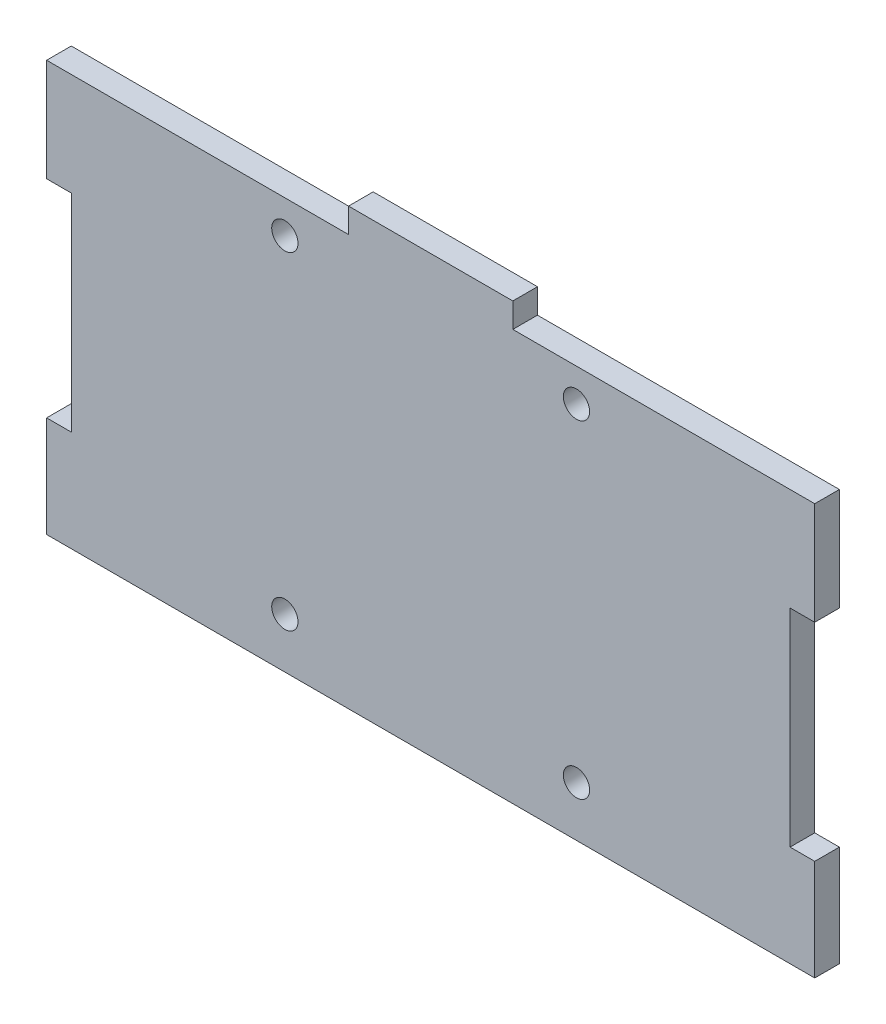
SolidWorks part; units mm, degrees
ref_plane "Plan de face" through (0, 0, 0) normal (0, 0, 1) x (1, 0, 0)
ref_plane "Plan de dessus" through (0, 0, 0) normal (0, 1, 0) x (1, 0, 0)
ref_plane "Plan de droite" through (0, 0, 0) normal (1, 0, 0) x (0, 0, -1)
sketch "Esquisse1" plane through (0, 0, 0) normal (0, 0, 1) x (1, 0, 0)
  line L1 (46.75, -25) -> (-46.75, -25)
  line L2 (46.75, -25) -> (46.75, -12.7)
  line L3 (46.75, 25) -> (26.2, 25)
  line L4 (-46.75, -25) -> (-46.75, -12.7)
  line L5 (46.75, -25) -> (-46.75, 25) construction
  line L6 (46.75, 25) -> (-46.75, -25) construction
  line L18 (0, 42.5868) -> (0, -42.8016) construction
  line L31 (-26.2, 25) -> (-46.75, 25)
  line L32 (23, 25) -> (-23, 25)
  line L33 (-46.75, -12.7) -> (-43.75, -12.7)
  line L34 (46.75, 12.5) -> (43.75, 12.5)
  line L36 (46.75, -12.7) -> (43.75, -12.7)
  line L37 (43.75, 12.5) -> (43.75, -12.7)
  line L38 (-43.75, 12.5) -> (-43.75, -12.7)
  line L39 (-46.75, 12.5) -> (-43.75, 12.5)
  line L41 (-46.75, 12.5) -> (-46.75, 25)
  line L42 (46.75, 12.5) -> (46.75, 25)
  line L43 (-26.2, 25) -> (-23, 25)
  line L44 (23, 25) -> (26.2, 25)
  point P0 (0, 0)
  dimension "D1" = 50
  dimension "D2" = 93.5
  dimension "D15" = 25.2
  dimension "D16" = 3
extrude "Boss.-Extru.1" add sketch "Esquisse1" along normal blind 3
sketch "Esquisse2" plane through (0, 0, 3) normal (0, 0, 1) x (1, 0, 0)
  line L0 (46.75, 25) -> (-46.75, 25) construction
  line L1 (-10, 25) -> (10, 25)
  line L2 (-10, 25) -> (-10, 28)
  line L3 (-10, 28) -> (10, 28)
  line L4 (10, 25) -> (10, 28)
  point P6 (0, 28)
  dimension "D1" = 20
  dimension "D2" = 3
extrude "Boss.-Extru.2" add sketch "Esquisse2" against normal blind 3
sketch "Sketch1" plane through (0, 0, 3) normal (0, 0, 1) x (1, 0, 0)
  circle A0 centre (-17.75, 21) radius 1.6
  point P3 (0, 0)
  dimension "D1" = 3.2
extrude "Cut-Extrude1" cut sketch "Sketch1" against normal through all
sketch "Sketch2" plane through (0, 0, 0) normal (0, 0, -1) x (-1, 0, 0)
  circle A0 centre (-17.75, 21) radius 1.6
  point P3 (-19.2235, 21.7773)
  point P4 (-17.75, 21)
extrude "Cut-Extrude2" cut sketch "Sketch2" against normal through all
sketch "Sketch3" plane through (0, 0, 3) normal (0, 0, 1) x (1, 0, 0)
  circle A0 centre (17.75, -18.9) radius 1.6
  circle A1 centre (-17.75, -18.9) radius 1.6
  point P6 (17.75, -18.9)
extrude "Cut-Extrude3" cut sketch "Sketch3" against normal through all
